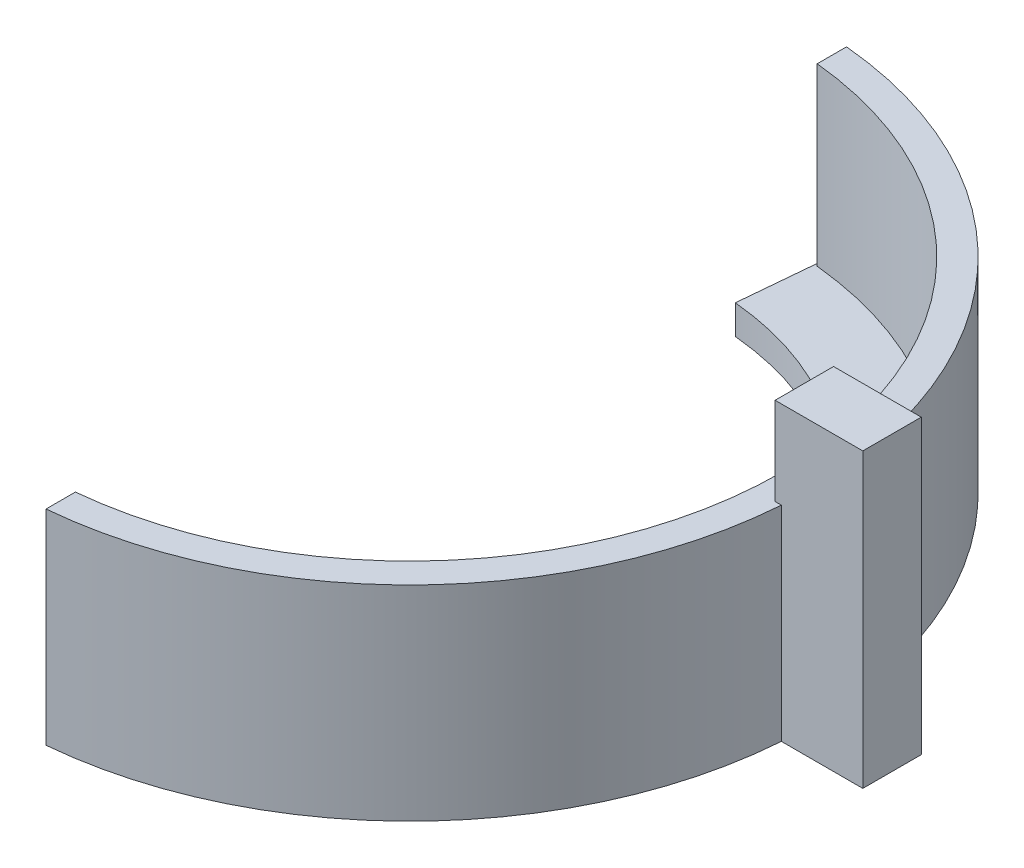
SolidWorks part; units mm, degrees
ref_plane "Front Plane" through (0, 0, 0) normal (0, 0, 1) x (1, 0, 0)
ref_plane "Top Plane" through (0, 0, 0) normal (0, 1, 0) x (1, 0, 0)
ref_plane "Right Plane" through (0, 0, 0) normal (1, 0, 0) x (0, 0, -1)
sketch "Sketch1" plane through (0, 0, 0) normal (0, 1, 0) x (1, 0, 0)
  line L4 (2.5, 27.3861) -> (2.5, 25.3772)
  line L6 (-2.5, 0) -> (2.5, 0) construction
  line L7 (2.5, -25.3772) -> (2.5, -27.3861)
  arc A2 (2.5, -27.3861) -> (2.5, 27.3861) centre (0, 0) ccw
  arc A5 (2.5, -25.3772) -> (2.5, 25.3772) centre (0, 0) ccw
  point P4 (24.3858, 7.4555)
  point P12 (26.2984, 8.0402)
extrude "Boss-Extrude3" add sketch "Sketch1" along normal blind 12
sketch "Sketch2" plane through (0, 0, 0) normal (0, 1, 0) x (1, 0, 0)
  line L0 (2.5, -25.3772) -> (2.5, -27.3861) construction
  line L1 (2.5, 27.3861) -> (1.8636, 20.4151)
  line L2 (2.5, -27.3861) -> (1.8636, -20.4151)
  arc A0 (2.5, 27.3861) -> (2.5, -27.3861) centre (0, 0) cw
  arc A1 (2.5, -27.3861) -> (2.5, 27.3861) centre (0, 0) ccw construction
  arc A2 (1.8636, 20.4151) -> (1.8636, -20.4151) centre (0, 0) cw
  dimension "D1" = 7
extrude "Boss-Extrude4" add sketch "Sketch2" against normal blind 2
sketch "Sketch3" plane through (0, -2, 0) normal (0, -1, 0) x (1, 0, 0)
  line L1 (27, -2) -> (33, -2)
  line L2 (27, -2) -> (27, 2)
  line L3 (27, 2) -> (33, 2)
  line L4 (33, -2) -> (33, 2)
  line L5 (30, 2) -> (30, -2) construction
  line L6 (27, 0) -> (33, 0) construction
  point P0 (30, 0)
  point P4 (0, 0)
  dimension "D1" = 30
  dimension "D2" = 4
  dimension "D3" = 6
extrude "Boss-Extrude5" add sketch "Sketch3" against normal blind 20
